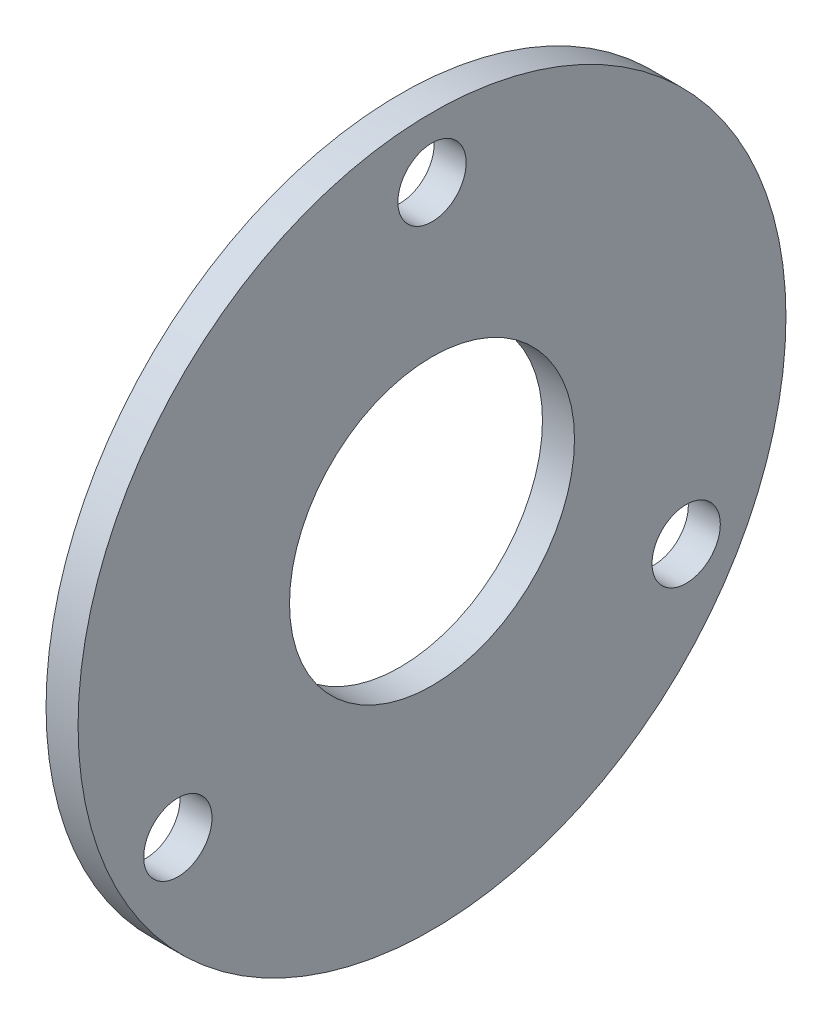
SolidWorks part; units mm, degrees
material "6061 Alloy"
ref_plane "Płaszczyzna przednia" through (0, 0, 0) normal (0, 0, 1) x (1, 0, 0)
ref_plane "Płaszczyzna górna" through (0, 0, 0) normal (0, 1, 0) x (1, 0, 0)
ref_plane "Płaszczyzna prawa" through (0, 0, 0) normal (1, 0, 0) x (0, 0, -1)
sketch "Szkic1" plane through (0, 0, 0) normal (0, 0, 1) x (1, 0, 0)
  line L0 (0, 0) -> (-56.1578, 0)
  line L11 (-31.5025, 13.351) -> (-31.5025, 33.166)
  line L12 (-31.5025, 13.351) -> (-31.5025, 0)
  line L13 (-28.5025, 0) -> (-28.5025, 33.166)
  line L15 (-31.5025, 33.166) -> (-28.5025, 33.166)
  line L16 (-31.5025, 13.351) -> (-28.5025, 13.351)
revolve "Obrót2" add sketch "Szkic1" angle 360 about L0
sketch "Szkic2" plane through (-28.5025, 0, 0) normal (1, 0, 0) x (0, 0, -1)
  line L0 (0, 0) -> (0, 27.5)
  circle A0 centre (0, 27.5) radius 3.2
  circle A1 centre (23.8157, -13.75) radius 3.2
  circle A2 centre (-23.8157, -13.75) radius 3.2
  point P11 (0, 0)
  dimension "D1" = 3
extrude "Wytnij-wyciągnięcie1" cut sketch "Szkic2" against normal through all
